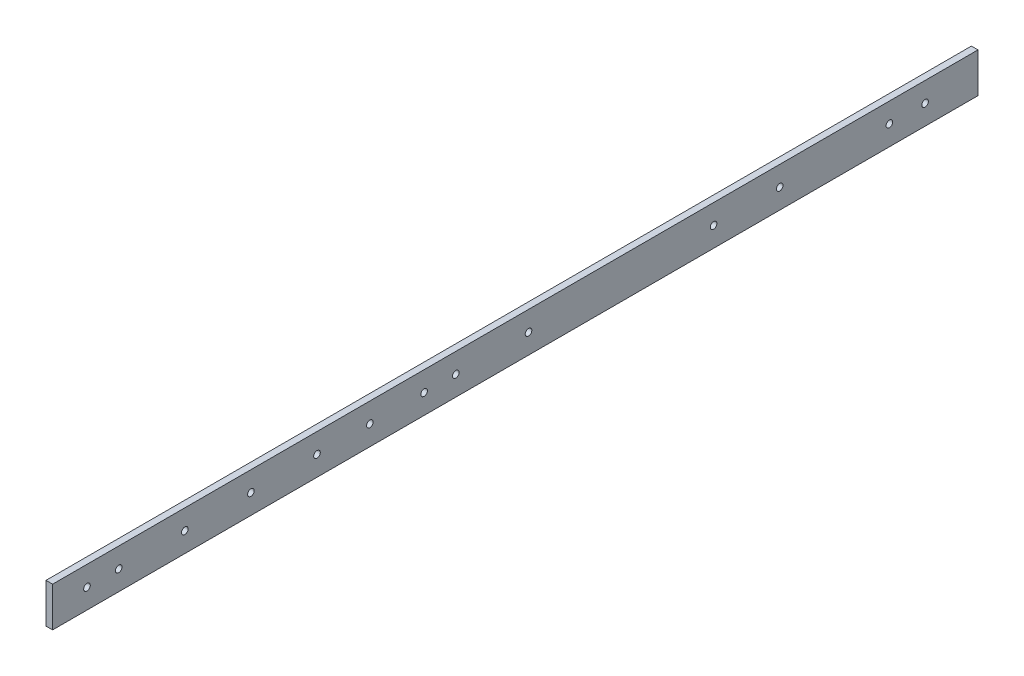
SolidWorks part; units mm, degrees
ref_plane "Front Plane" through (0, 0, 0) normal (0, 0, 1) x (1, 0, 0)
ref_plane "Top Plane" through (0, 0, 0) normal (0, 1, 0) x (1, 0, 0)
ref_plane "Right Plane" through (0, 0, 0) normal (1, 0, 0) x (0, 0, -1)
sketch "Sketch1" plane through (0, 0, 0) normal (0, 0, 1) x (1, 0, 0)
  line L1 (0, 0) -> (5, 0)
  line L2 (0, 0) -> (0, 30)
  line L3 (0, 30) -> (5, 30)
  line L4 (5, 0) -> (5, 30)
  dimension "D1" = 30
  dimension "D2" = 5
extrude "Boss-Extrude1" add sketch "Sketch1" along normal blind 700
sketch "Sketch2" plane through (5, 0, 0) normal (1, 0, 0) x (0, 0, -1)
  line L0 (-700, 15) -> (0, 15) construction
  line L1 (-700, 0) -> (-700, 30) construction
  line L2 (0, 0) -> (0, 30) construction
  circle A0 centre (-674, 15) radius 2.5
  circle A1 centre (-600, 15) radius 2.5
  circle A2 centre (-500, 15) radius 2.5
  circle A3 centre (-550, 15) radius 2.5
  circle A4 centre (-460, 15) radius 2.5
  circle A5 centre (-419, 15) radius 2.5
  circle A6 centre (-395, 15) radius 2.5
  circle A7 centre (-340, 15) radius 2.5
  circle A8 centre (-200, 15) radius 2.5
  circle A9 centre (-650, 15) radius 2.5
  circle A10 centre (-150, 15) radius 2.5
  circle A11 centre (-67, 15) radius 2.5
  circle A13 centre (-40, 15) radius 2.5
  dimension "D10" = 500
  dimension "D14" = 5
  dimension "D15" = 5
  dimension "D1" = 26
  dimension "D2" = 100
  dimension "D3" = 150
  dimension "D4" = 200
  dimension "D5" = 240
  dimension "D6" = 50
  dimension "D7" = 281
  dimension "D8" = 305
  dimension "D9" = 360
  dimension "D11" = 550
  dimension "D12" = 633
  dimension "D13" = 660
extrude "Cut-Extrude1" cut sketch "Sketch2" against normal through all contours A0 | A9 | A1 | A3 | A2 | A4 | A5 | A6 | A7 | A13 | A10 | A8 | A11
